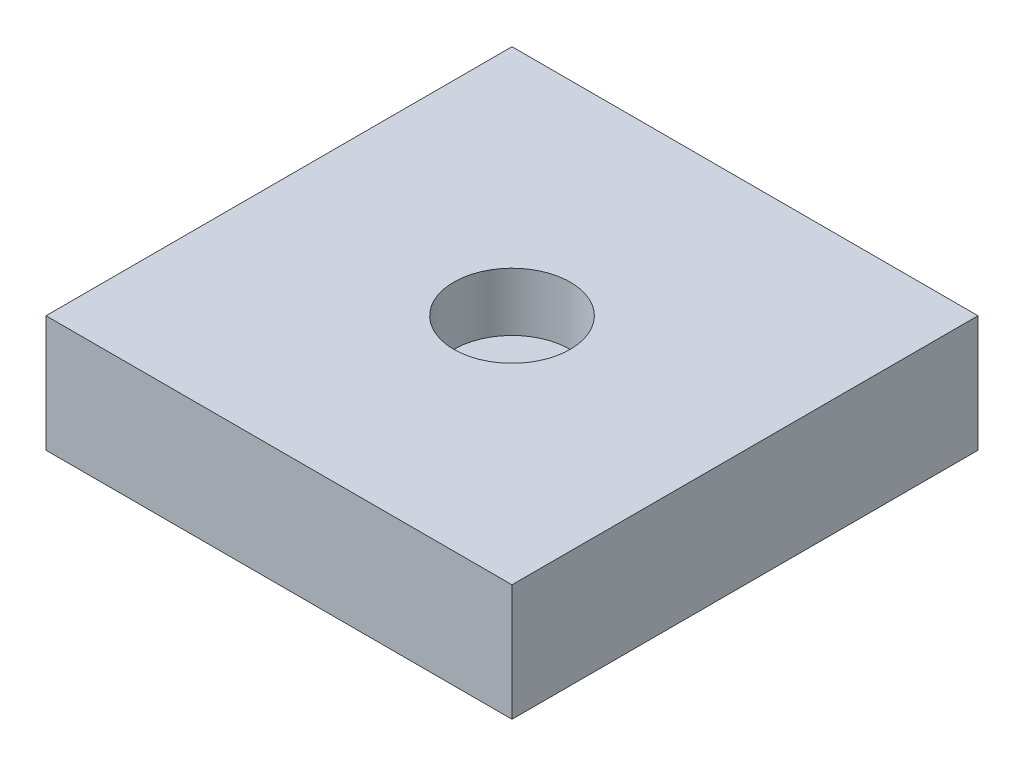
SolidWorks part; units mm, degrees
ref_plane "Front Plane" through (0, 0, 0) normal (0, 0, 1) x (1, 0, 0)
ref_plane "Top Plane" through (0, 0, 0) normal (0, 1, 0) x (1, 0, 0)
ref_plane "Right Plane" through (0, 0, 0) normal (1, 0, 0) x (0, 0, -1)
sketch "Sketch1" plane through (0, 0, 0) normal (0, 1, 0) x (1, 0, 0)
  line L1 (-25.4, -25.4) -> (25.4, -25.4)
  line L2 (-25.4, -25.4) -> (-25.4, 25.4)
  line L3 (-25.4, 25.4) -> (25.4, 25.4)
  line L4 (25.4, -25.4) -> (25.4, 25.4)
  line L5 (-25.4, -25.4) -> (25.4, 25.4) construction
  line L6 (-25.4, 25.4) -> (25.4, -25.4) construction
  point P0 (0, 0)
  dimension "D1" = 50.8
  dimension "D2" = 50.8
extrude "Boss-Extrude1" add sketch "Sketch1" along normal blind 12.7
sketch "Sketch2" plane through (0, 12.7, 0) normal (0, 1, 0) x (1, 0, 0)
  circle A0 centre (0, 0) radius 6.35
  dimension "D1" = 12.7
extrude "Cut-Extrude1" cut sketch "Sketch2" against normal blind 6.35
